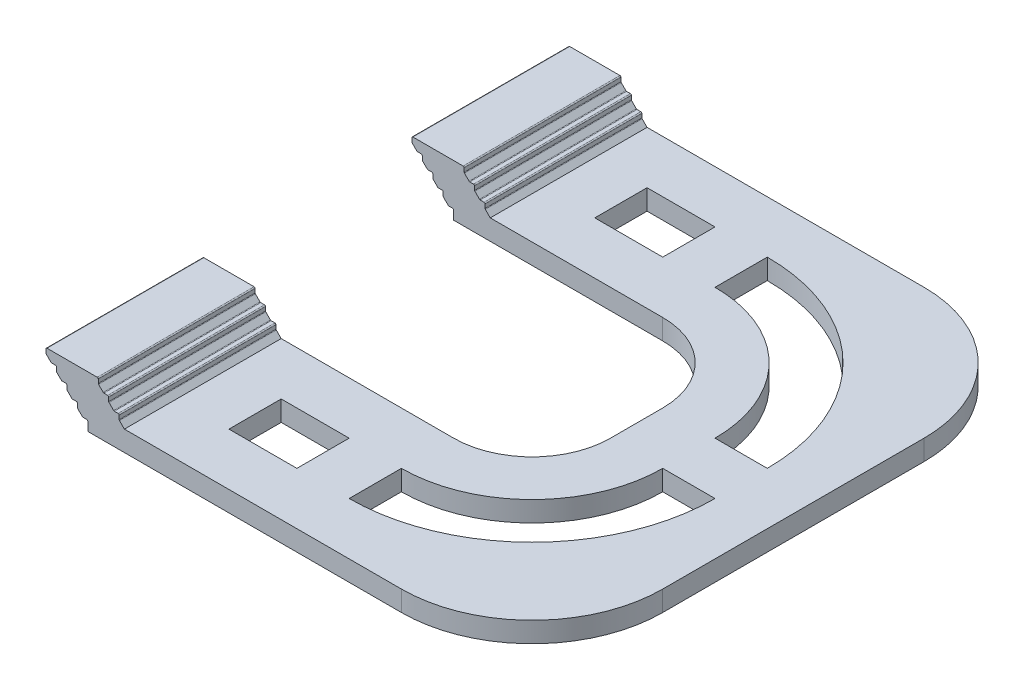
SolidWorks part; units mm, degrees
ref_plane "Front Plane" through (0, 0, 0) normal (0, 0, 1) x (1, 0, 0)
ref_plane "Top Plane" through (0, 0, 0) normal (0, 1, 0) x (1, 0, 0)
ref_plane "Right Plane" through (0, 0, 0) normal (1, 0, 0) x (0, 0, -1)
sketch "Sketch1" plane through (0, 0, 0) normal (0, 0, 1) x (1, 0, 0)
  line L0 (-25.7423, -27.4955) -> (-25.7423, -25.8038)
  line L12 (-27.7423, -24.521) -> (-27.7423, -23.8038)
  line L13 (-33.5423, -17.6038) -> (-23.9423, -17.6038)
  line L14 (-18.7423, -23.6038) -> (-19.6837, -22.6624)
  line L24 (-17.7423, -23.6038) -> (-18.7423, -23.6038)
  line L27 (-23.7423, -18.521) -> (-23.7423, -17.8038)
  line L28 (-19.9423, -21.6038) -> (-20.6594, -21.6038)
  line L29 (-20.8009, -21.5453) -> (-21.6837, -20.6624)
  line L30 (-22.8009, -19.5453) -> (-23.6837, -18.6624)
  line L31 (-21.7423, -20.521) -> (-21.7423, -19.8038)
  line L32 (-21.9423, -19.6038) -> (-22.6594, -19.6038)
  line L33 (-19.7423, -22.521) -> (-19.7423, -21.8038)
  line L35 (59.2577, -27.4955) -> (59.2577, -23.6038)
  line L39 (59.2577, -23.6038) -> (-17.7423, -23.6038)
  line L40 (-25.7423, -27.4955) -> (59.2577, -27.4955)
  line L41 (-26.8009, -25.5453) -> (-27.6837, -24.6624)
  line L47 (-25.9423, -25.6038) -> (-26.6594, -25.6038)
  line L49 (-29.7423, -22.521) -> (-29.7423, -21.8038)
  line L50 (-27.9423, -23.6038) -> (-28.6594, -23.6038)
  line L51 (-28.8009, -23.5453) -> (-29.6837, -22.6624)
  line L52 (-30.8009, -21.5453) -> (-31.6837, -20.6624)
  line L53 (-31.7423, -20.521) -> (-31.7423, -19.8038)
  line L54 (-29.9423, -21.6038) -> (-30.6594, -21.6038)
  line L55 (-32.8009, -19.5453) -> (-33.6837, -18.6624)
  line L56 (-31.9423, -19.6038) -> (-32.6594, -19.6038)
  line L57 (-33.7423, -18.521) -> (-33.7423, -17.8038)
  arc A0 (-33.7423, -17.8038) -> (-33.5423, -17.6038) centre (-33.5423, -17.8038) cw
  arc A1 (-31.7423, -19.8038) -> (-31.9423, -19.6038) centre (-31.9423, -19.8038) ccw
  arc A2 (-29.7423, -21.8038) -> (-29.9423, -21.6038) centre (-29.9423, -21.8038) ccw
  arc A3 (-27.7423, -23.8038) -> (-27.9423, -23.6038) centre (-27.9423, -23.8038) ccw
  arc A4 (-25.7423, -25.8038) -> (-25.9423, -25.6038) centre (-25.9423, -25.8038) ccw
  arc A5 (-19.9423, -21.6038) -> (-19.7423, -21.8038) centre (-19.9423, -21.8038) cw
  arc A6 (-21.7423, -19.8038) -> (-21.9423, -19.6038) centre (-21.9423, -19.8038) ccw
  arc A7 (-23.9423, -17.6038) -> (-23.7423, -17.8038) centre (-23.9423, -17.8038) cw
  arc A10 (-19.6837, -22.6624) -> (-19.7423, -22.521) centre (-19.5423, -22.521) cw
  arc A11 (-20.6594, -21.6038) -> (-20.8009, -21.5453) centre (-20.6594, -21.4038) cw
  arc A12 (-21.6837, -20.6624) -> (-21.7423, -20.521) centre (-21.5423, -20.521) cw
  arc A13 (-22.8009, -19.5453) -> (-22.6594, -19.6038) centre (-22.6594, -19.4038) ccw
  arc A14 (-23.7423, -18.521) -> (-23.6837, -18.6624) centre (-23.5423, -18.521) ccw
  arc A15 (-26.8009, -25.5453) -> (-26.6594, -25.6038) centre (-26.6594, -25.4038) ccw
  arc A16 (-27.6837, -24.6624) -> (-27.7423, -24.521) centre (-27.5423, -24.521) cw
  arc A17 (-28.6594, -23.6038) -> (-28.8009, -23.5453) centre (-28.6594, -23.4038) cw
  arc A18 (-29.7423, -22.521) -> (-29.6837, -22.6624) centre (-29.5423, -22.521) ccw
  arc A19 (-30.8009, -21.5453) -> (-30.6594, -21.6038) centre (-30.6594, -21.4038) ccw
  arc A20 (-31.6837, -20.6624) -> (-31.7423, -20.521) centre (-31.5423, -20.521) cw
  arc A21 (-32.8009, -19.5453) -> (-32.6594, -19.6038) centre (-32.6594, -19.4038) ccw
  arc A22 (-33.6837, -18.6624) -> (-33.7423, -18.521) centre (-33.5423, -18.521) cw
  point P25 (-29.2423, -23.1038)
  point P60 (-27.2423, -25.1038)
  dimension "D1" = 0.2
  dimension "D2" = 0.2
extrude "Boss-Extrude1" add sketch "Sketch1" along normal blind 100
sketch "Sketch2" plane through (0, -23.6038, 0) normal (0, 1, 0) x (1, 0, 0)
  line L0 (14.2577, -30) -> (-42.6227, -30)
  line L15 (-42.6227, -30) -> (-42.6227, -70)
  line L16 (-42.6227, -70) -> (14.2577, -70)
  line L17 (29.2577, -55) -> (29.2577, -45)
  arc A0 (14.2577, -70) -> (29.2577, -55) centre (14.2577, -55) ccw
  arc A1 (29.2577, -45) -> (14.2577, -30) centre (14.2577, -45) ccw
  dimension "D1" = 15
extrude "Cut-Extrude1" cut sketch "Sketch2" against normal blind 24 and the other way blind 24
fillet "Fillet2" radius 25 2 edges at (59.2577, -25.5497, 100) (59.2577, -25.5497, 0)
sketch "Sketch4" plane through (0, -23.6038, 0) normal (0, 1, 0) x (1, 0, 0)
  line L1 (14.2577, -90) -> (14.2577, -80)
  line L2 (39.2577, -55) -> (49.2577, -55)
  line L9 (14.2577, -80) -> (14.2577, -90)
  line L23 (59.2577, -50) -> (-53.4253, -50) construction
  line L28 (59.2577, -75) -> (59.2577, -25) construction
  line L30 (4.2577, -80) -> (-8.7423, -80)
  line L31 (-8.7423, -90) -> (4.2577, -90)
  line L32 (-8.7423, -80) -> (-8.7423, -90)
  line L33 (4.2577, -90) -> (4.2577, -80)
  line L34 (4.2577, -10) -> (4.2577, -20)
  line L35 (-8.7423, -20) -> (-8.7423, -10)
  line L36 (-8.7423, -10) -> (4.2577, -10)
  line L37 (4.2577, -20) -> (-8.7423, -20)
  line L38 (14.2577, -20) -> (14.2577, -10)
  line L39 (39.2577, -45) -> (49.2577, -45)
  line L40 (14.2577, -10) -> (14.2577, -20)
  arc A0 (14.2577, -10) -> (49.2577, -45) centre (14.2577, -45) cw
  arc A1 (14.2577, -20) -> (39.2577, -45) centre (14.2577, -45) cw
  arc A2 (14.2577, -80) -> (39.2577, -55) centre (14.2577, -55) ccw
  arc A3 (14.2577, -90) -> (49.2577, -55) centre (14.2577, -55) ccw
extrude "Cut-Extrude3" cut sketch "Sketch4" against normal blind 23 contours L1 A3 L2 A2 | L31 L33 L30 L32 | L38 A1 L39 A0 | L37 L34 L36 L35
